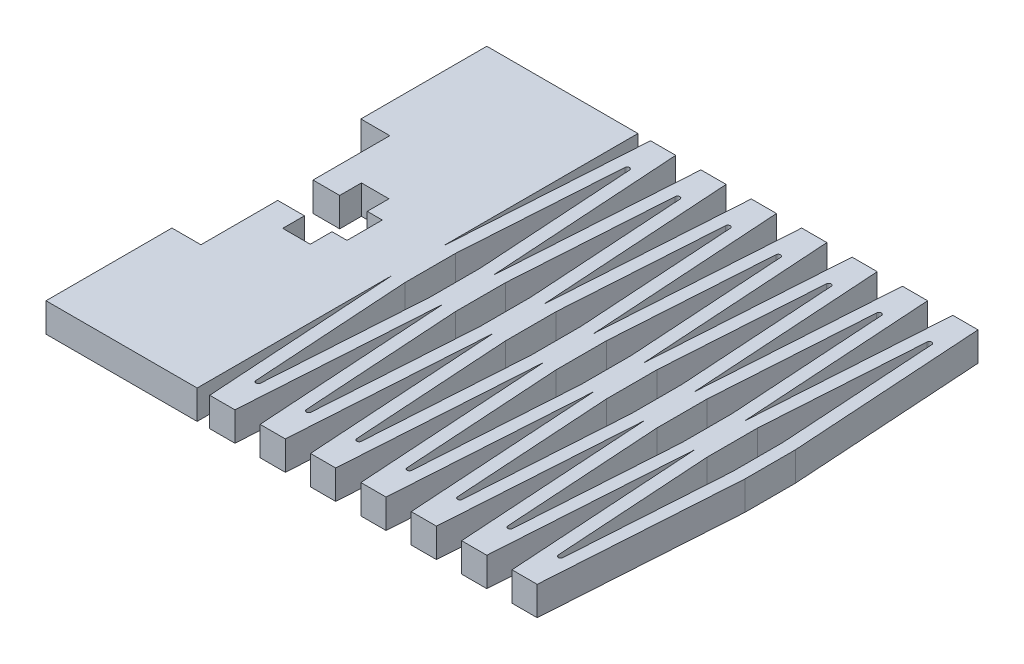
SolidWorks part; units mm, degrees
ref_plane "Front Plane" through (0, 0, 0) normal (0, 0, 1) x (1, 0, 0)
ref_plane "Top Plane" through (0, 0, 0) normal (0, 1, 0) x (1, 0, 0)
ref_plane "Right Plane" through (0, 0, 0) normal (1, 0, 0) x (0, 0, -1)
sketch "Sketch2" plane through (0, 0, 0) normal (0, 1, 0) x (1, 0, 0)
  line L0 (50.8, 22.225) -> (-18.5498, 22.225) construction
  line L1 (50.8, 24.765) -> (-21.0766, 24.765) construction
  line L2 (0, 12.7) -> (2.921, 12.7)
  line L3 (0, 31.75) -> (2.921, 31.75)
  line L4 (2.921, 12.7) -> (2.921, 20.447)
  line L5 (2.921, 20.447) -> (5.6123, 20.447)
  line L6 (5.6123, 24.003) -> (5.6123, 26.1937)
  line L7 (2.921, 24.003) -> (5.6123, 24.003)
  line L8 (9.906, 20.447) -> (9.906, 24.003)
  line L9 (2.921, 24.003) -> (2.921, 31.75)
  line L10 (5.6123, 18.2562) -> (8.3905, 18.2562)
  line L11 (5.6123, 18.2562) -> (5.6123, 20.447)
  line L12 (5.6123, 26.1937) -> (8.3905, 26.1937)
  line L13 (8.3905, 18.2562) -> (8.3905, 20.447)
  line L14 (8.3905, 24.003) -> (8.3905, 26.1937)
  line L15 (8.3905, 20.447) -> (9.906, 20.447)
  line L16 (8.3905, 24.003) -> (9.906, 24.003)
  line L17 (0, 12.7) -> (0, 0)
  line L18 (0, 44.45) -> (15.24, 44.45)
  line L19 (0, 44.45) -> (0, 31.75)
  line L20 (0, 0) -> (15.24, 0)
  line L21 (50.8, 44.45) -> (50.8, 0) construction
  line L22 (50.8, 19.685) -> (-16.0862, 19.685) construction
  line L23 (50.8, 24.765) -> (49.53, 44.45)
  line L24 (46.99, 44.45) -> (45.72, 24.765)
  line L25 (48.0256, 40.8172) -> (46.99, 24.765)
  line L26 (48.4944, 40.8172) -> (49.53, 24.765)
  line L27 (48.0256, 3.6328) -> (46.99, 19.685)
  line L28 (48.4944, 3.6328) -> (49.53, 19.685)
  line L29 (50.8, 24.765) -> (50.8, 19.685)
  line L30 (50.8, 19.685) -> (49.53, 0)
  line L31 (46.99, 0) -> (45.72, 19.685)
  line L32 (46.99, 24.765) -> (46.99, 19.685)
  line L33 (49.53, 24.765) -> (49.53, 19.685)
  line L34 (41.91, 44.45) -> (40.64, 24.765)
  line L35 (42.9456, 40.8172) -> (41.91, 24.765)
  line L36 (43.4144, 40.8172) -> (44.45, 24.765)
  line L37 (45.72, 24.765) -> (44.45, 44.45)
  line L38 (44.45, 24.765) -> (44.45, 19.685)
  line L39 (41.91, 24.765) -> (41.91, 19.685)
  line L40 (41.91, 0) -> (40.64, 19.685)
  line L41 (43.4144, 3.6328) -> (44.45, 19.685)
  line L42 (42.9456, 3.6328) -> (41.91, 19.685)
  line L43 (45.72, 19.685) -> (44.45, 0)
  line L44 (36.83, 44.45) -> (35.56, 24.765)
  line L45 (37.8656, 40.8172) -> (36.83, 24.765)
  line L46 (38.3344, 40.8172) -> (39.37, 24.765)
  line L47 (40.64, 24.765) -> (39.37, 44.45)
  line L48 (39.37, 24.765) -> (39.37, 19.685)
  line L49 (36.83, 24.765) -> (36.83, 19.685)
  line L50 (36.83, 0) -> (35.56, 19.685)
  line L51 (38.3344, 3.6328) -> (39.37, 19.685)
  line L52 (37.8656, 3.6328) -> (36.83, 19.685)
  line L53 (40.64, 19.685) -> (39.37, 0)
  line L54 (31.75, 44.45) -> (30.48, 24.765)
  line L55 (32.7856, 40.8172) -> (31.75, 24.765)
  line L56 (33.2544, 40.8172) -> (34.29, 24.765)
  line L57 (35.56, 24.765) -> (34.29, 44.45)
  line L58 (34.29, 24.765) -> (34.29, 19.685)
  line L59 (31.75, 24.765) -> (31.75, 19.685)
  line L60 (31.75, 0) -> (30.48, 19.685)
  line L61 (33.2544, 3.6328) -> (34.29, 19.685)
  line L62 (32.7856, 3.6328) -> (31.75, 19.685)
  line L63 (35.56, 19.685) -> (34.29, 0)
  line L64 (26.67, 44.45) -> (25.4, 24.765)
  line L65 (27.7056, 40.8172) -> (26.67, 24.765)
  line L66 (28.1744, 40.8172) -> (29.21, 24.765)
  line L67 (30.48, 24.765) -> (29.21, 44.45)
  line L68 (29.21, 24.765) -> (29.21, 19.685)
  line L69 (26.67, 24.765) -> (26.67, 19.685)
  line L70 (26.67, 0) -> (25.4, 19.685)
  line L71 (28.1744, 3.6328) -> (29.21, 19.685)
  line L72 (27.7056, 3.6328) -> (26.67, 19.685)
  line L73 (30.48, 19.685) -> (29.21, 0)
  line L74 (21.59, 44.45) -> (20.32, 24.765)
  line L75 (22.6256, 40.8172) -> (21.59, 24.765)
  line L76 (23.0944, 40.8172) -> (24.13, 24.765)
  line L77 (25.4, 24.765) -> (24.13, 44.45)
  line L78 (24.13, 24.765) -> (24.13, 19.685)
  line L79 (21.59, 24.765) -> (21.59, 19.685)
  line L80 (21.59, 0) -> (20.32, 19.685)
  line L81 (23.0944, 3.6328) -> (24.13, 19.685)
  line L82 (22.6256, 3.6328) -> (21.59, 19.685)
  line L83 (25.4, 19.685) -> (24.13, 0)
  line L84 (16.51, 44.45) -> (15.24, 24.765)
  line L85 (17.5456, 40.8172) -> (16.51, 24.765)
  line L86 (18.0144, 40.8172) -> (19.05, 24.765)
  line L87 (20.32, 24.765) -> (19.05, 44.45)
  line L88 (19.05, 24.765) -> (19.05, 19.685)
  line L89 (16.51, 24.765) -> (16.51, 19.685)
  line L90 (16.51, 0) -> (15.24, 19.685)
  line L91 (18.0144, 3.6328) -> (19.05, 19.685)
  line L92 (17.5456, 3.6328) -> (16.51, 19.685)
  line L93 (20.32, 19.685) -> (19.05, 0)
  line L94 (21.59, 0) -> (24.13, 0)
  line L95 (26.67, 0) -> (29.21, 0)
  line L96 (31.75, 0) -> (34.29, 0)
  line L97 (36.83, 0) -> (39.37, 0)
  line L98 (41.91, 0) -> (44.45, 0)
  line L99 (46.99, 0) -> (49.53, 0)
  line L100 (21.59, 44.45) -> (24.13, 44.45)
  line L101 (26.67, 44.45) -> (29.21, 44.45)
  line L102 (31.75, 44.45) -> (34.29, 44.45)
  line L103 (36.83, 44.45) -> (39.37, 44.45)
  line L104 (41.91, 44.45) -> (44.45, 44.45)
  line L105 (46.99, 44.45) -> (49.53, 44.45)
  line L106 (15.24, 19.685) -> (15.24, 0)
  line L107 (15.24, 24.765) -> (15.24, 44.45)
  line L108 (16.51, 0) -> (19.05, 0)
  line L109 (16.51, 44.45) -> (19.05, 44.45)
  arc A0 (48.0256, 40.8172) -> (48.4944, 40.8172) centre (48.26, 40.8172) cw
  arc A1 (48.0256, 3.6328) -> (48.4944, 3.6328) centre (48.26, 3.6328) ccw
  arc A2 (42.9456, 3.6328) -> (43.4144, 3.6328) centre (43.18, 3.6328) ccw
  arc A3 (42.9456, 40.8172) -> (43.4144, 40.8172) centre (43.18, 40.8172) cw
  arc A4 (37.8656, 3.6328) -> (38.3344, 3.6328) centre (38.1, 3.6328) ccw
  arc A5 (37.8656, 40.8172) -> (38.3344, 40.8172) centre (38.1, 40.8172) cw
  arc A6 (32.7856, 3.6328) -> (33.2544, 3.6328) centre (33.02, 3.6328) ccw
  arc A7 (32.7856, 40.8172) -> (33.2544, 40.8172) centre (33.02, 40.8172) cw
  arc A8 (27.7056, 3.6328) -> (28.1744, 3.6328) centre (27.94, 3.6328) ccw
  arc A9 (27.7056, 40.8172) -> (28.1744, 40.8172) centre (27.94, 40.8172) cw
  arc A10 (22.6256, 3.6328) -> (23.0944, 3.6328) centre (22.86, 3.6328) ccw
  arc A11 (22.6256, 40.8172) -> (23.0944, 40.8172) centre (22.86, 40.8172) cw
  arc A12 (17.5456, 3.6328) -> (18.0144, 3.6328) centre (17.78, 3.6328) ccw
  arc A13 (17.5456, 40.8172) -> (18.0144, 40.8172) centre (17.78, 40.8172) cw
  point P2 (-84.4722, -3.155)
  point P11 (-77.4708, -3.155)
  dimension "D1" = 44.45
  dimension "D2" = 19.05
  dimension "D3" = 6.985
  dimension "D4" = 2.7781
  dimension "D5" = 0
  dimension "D6" = 12.7
  dimension "D7" = 7.747
  dimension "D8" = 7.747
  dimension "D9" = 2.6913
  dimension "D10" = 2.921
  dimension "D11" = 2.1907
  dimension "D12" = 2.1908
  dimension "D13" = 50.8
  dimension "D14" = 2.54
  dimension "D15" = 7
  dimension "D16" = 1.27
  dimension "D17" = 2.54
  dimension "D18" = 5.08
  dimension "D19" = 1.27
  dimension "D20" = 1.27
extrude "Boss-Extrude1" add sketch "Sketch2" along normal blind 2.921
